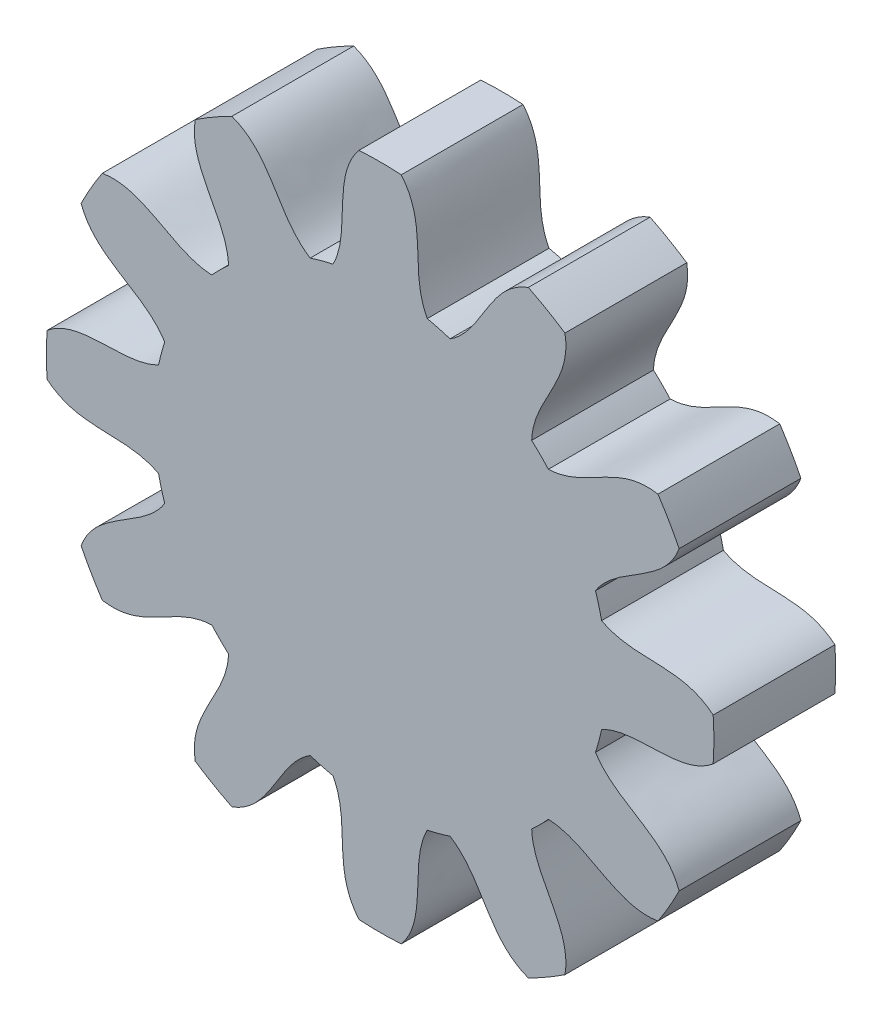
SolidWorks part; units mm, degrees
ref_plane "前视基准面" through (0, 0, 0) normal (0, 0, 1) x (1, 0, 0)
ref_plane "上视基准面" through (0, 0, 0) normal (0, 1, 0) x (1, 0, 0)
ref_plane "右视基准面" through (0, 0, 0) normal (1, 0, 0) x (0, 0, -1)
sketch "草图1" plane through (0, 0, 0) normal (0, 0, 1) x (1, 0, 0)
  line L0 (0, 11.2324) -> (0, -12.9546) construction
  line L1 (0, 16.8486) -> (0, -19.4319) construction
  circle A0 centre (0, 0) radius 7.2 construction
  arc A1 (-3.7303, 7.5263) -> (-4.6528, 6.9937) centre (0, 0) ccw
  arc A2 (-1.1862, 5.5752) -> (-1.7603, 5.4214) centre (0, 0) ccw
  arc A3 (0.5326, 8.3831) -> (-0.5326, 8.3831) centre (0, 0) ccw
  arc A4 (1.7603, 5.4214) -> (1.1862, 5.5752) centre (0, 0) ccw
  arc A5 (4.6528, 6.9937) -> (3.7303, 7.5263) centre (0, 0) ccw
  arc A6 (4.2352, 3.8149) -> (3.8149, 4.2352) centre (0, 0) ccw
  arc A7 (7.5263, 3.7303) -> (6.9937, 4.6528) centre (0, 0) ccw
  arc A8 (5.5752, 1.1862) -> (5.4214, 1.7603) centre (0, 0) ccw
  arc A9 (8.3831, -0.5326) -> (8.3831, 0.5326) centre (0, 0) ccw
  arc A10 (5.4214, -1.7603) -> (5.5752, -1.1862) centre (0, 0) ccw
  arc A11 (6.9937, -4.6528) -> (7.5263, -3.7303) centre (0, 0) ccw
  arc A12 (3.8149, -4.2352) -> (4.2352, -3.8149) centre (0, 0) ccw
  arc A13 (3.7303, -7.5263) -> (4.6528, -6.9937) centre (0, 0) ccw
  arc A14 (1.1862, -5.5752) -> (1.7603, -5.4214) centre (0, 0) ccw
  arc A15 (-0.5326, -8.3831) -> (0.5326, -8.3831) centre (0, 0) ccw
  arc A16 (-1.7603, -5.4214) -> (-1.1862, -5.5752) centre (0, 0) ccw
  arc A17 (-4.6528, -6.9937) -> (-3.7303, -7.5263) centre (0, 0) ccw
  arc A18 (-4.2352, -3.8149) -> (-3.8149, -4.2352) centre (0, 0) ccw
  arc A19 (-7.5263, -3.7303) -> (-6.9937, -4.6528) centre (0, 0) ccw
  arc A20 (-5.5752, -1.1862) -> (-5.4214, -1.7603) centre (0, 0) ccw
  arc A21 (-8.3831, 0.5326) -> (-8.3831, -0.5326) centre (0, 0) ccw
  arc A22 (-5.4214, 1.7603) -> (-5.5752, 1.1862) centre (0, 0) ccw
  arc A23 (-6.9937, 4.6528) -> (-7.5263, 3.7303) centre (0, 0) ccw
  arc A24 (-3.8149, 4.2352) -> (-4.2352, 3.8149) centre (0, 0) ccw
  arc A25 (-2.6404, -8.1321) -> (-1.7793, -8.3628) centre (0, 0) ccw
  arc A26 (-11.2894, -5.5954) -> (-10.4905, -6.9792) centre (0, 0) ccw
  arc A27 (-12.5746, 0.7989) -> (-12.5746, -0.7989) centre (0, 0) ccw
  arc A28 (8.3628, 1.7793) -> (8.1321, 2.6404) centre (0, 0) ccw
  arc A29 (-10.4905, 6.9792) -> (-11.2894, 5.5954) centre (0, 0) ccw
  arc A30 (6.3527, 5.7224) -> (5.7224, 6.3527) centre (0, 0) ccw
  arc A31 (10.4905, -6.9792) -> (11.2894, -5.5954) centre (0, 0) ccw
  arc A32 (-5.7224, 6.3527) -> (-6.3527, 5.7224) centre (0, 0) ccw
  circle A33 centre (0, 0) radius 10.8 construction
  arc A34 (11.2894, 5.5954) -> (10.4905, 6.9792) centre (0, 0) ccw
  arc A35 (5.7224, -6.3527) -> (6.3527, -5.7224) centre (0, 0) ccw
  arc A36 (1.7793, -8.3628) -> (2.6404, -8.1321) centre (0, 0) ccw
  arc A37 (-1.7793, 8.3628) -> (-2.6404, 8.1321) centre (0, 0) ccw
  arc A38 (2.6404, 8.1321) -> (1.7793, 8.3628) centre (0, 0) ccw
  arc A39 (8.1321, -2.6404) -> (8.3628, -1.7793) centre (0, 0) ccw
  arc A40 (-8.1321, 2.6404) -> (-8.3628, 1.7793) centre (0, 0) ccw
  arc A41 (0.7989, 12.5746) -> (-0.7989, 12.5746) centre (0, 0) ccw
  arc A42 (5.5954, -11.2894) -> (6.9792, -10.4905) centre (0, 0) ccw
  arc A43 (-0.7989, -12.5746) -> (0.7989, -12.5746) centre (0, 0) ccw
  arc A44 (-6.3527, -5.7224) -> (-5.7224, -6.3527) centre (0, 0) ccw
  arc A45 (-8.3628, -1.7793) -> (-8.1321, -2.6404) centre (0, 0) ccw
  arc A46 (-5.5954, 11.2894) -> (-6.9792, 10.4905) centre (0, 0) ccw
  arc A47 (12.5746, -0.7989) -> (12.5746, 0.7989) centre (0, 0) ccw
  arc A48 (-6.9792, -10.4905) -> (-5.5954, -11.2894) centre (0, 0) ccw
  arc A49 (6.9792, 10.4905) -> (5.5954, 11.2894) centre (0, 0) ccw
  spline S0 degree 3 poles (-0.5326, 8.3831) (-1.2254, 7.5539) (-0.7219, 6.4463) (-1.1862, 5.5752) knots 0 0 0 0 1 1 1 1
  spline S1 degree 3 poles (0.5326, 8.3831) (1.2254, 7.5539) (0.7219, 6.4463) (1.1862, 5.5752) knots 0 0 0 0 1 1 1 1
  spline S2 degree 3 poles (3.7303, 7.5263) (2.7157, 7.1545) (2.598, 5.9436) (1.7603, 5.4214) knots 0 0 0 0 1 1 1 1
  spline S3 degree 3 poles (4.6528, 6.9937) (4.8381, 5.9291) (3.8484, 5.2217) (3.8149, 4.2352) knots 0 0 0 0 1 1 1 1
  spline S4 degree 3 poles (6.9937, 4.6528) (5.9291, 4.8381) (5.2217, 3.8484) (4.2352, 3.8149) knots 0 0 0 0 1 1 1 1
  spline S5 degree 3 poles (7.5263, 3.7303) (7.1545, 2.7157) (5.9436, 2.598) (5.4214, 1.7603) knots 0 0 0 0 1 1 1 1
  spline S6 degree 3 poles (8.3831, 0.5326) (7.5539, 1.2254) (6.4463, 0.7219) (5.5752, 1.1862) knots 0 0 0 0 1 1 1 1
  spline S7 degree 3 poles (8.3831, -0.5326) (7.5539, -1.2254) (6.4463, -0.7219) (5.5752, -1.1862) knots 0 0 0 0 1 1 1 1
  spline S8 degree 3 poles (7.5263, -3.7303) (7.1545, -2.7157) (5.9436, -2.598) (5.4214, -1.7603) knots 0 0 0 0 1 1 1 1
  spline S9 degree 3 poles (6.9937, -4.6528) (5.9291, -4.8381) (5.2217, -3.8484) (4.2352, -3.8149) knots 0 0 0 0 1 1 1 1
  spline S10 degree 3 poles (4.6528, -6.9937) (4.8381, -5.9291) (3.8484, -5.2217) (3.8149, -4.2352) knots 0 0 0 0 1 1 1 1
  spline S11 degree 3 poles (3.7303, -7.5263) (2.7157, -7.1545) (2.598, -5.9436) (1.7603, -5.4214) knots 0 0 0 0 1 1 1 1
  spline S12 degree 3 poles (0.5326, -8.3831) (1.2254, -7.5539) (0.7219, -6.4463) (1.1862, -5.5752) knots 0 0 0 0 1 1 1 1
  spline S13 degree 3 poles (-0.5326, -8.3831) (-1.2254, -7.5539) (-0.7219, -6.4463) (-1.1862, -5.5752) knots 0 0 0 0 1 1 1 1
  spline S14 degree 3 poles (-3.7303, -7.5263) (-2.7157, -7.1545) (-2.598, -5.9436) (-1.7603, -5.4214) knots 0 0 0 0 1 1 1 1
  spline S15 degree 3 poles (-4.6528, -6.9937) (-4.8381, -5.9291) (-3.8484, -5.2217) (-3.8149, -4.2352) knots 0 0 0 0 1 1 1 1
  spline S16 degree 3 poles (-6.9937, -4.6528) (-5.9291, -4.8381) (-5.2217, -3.8484) (-4.2352, -3.8149) knots 0 0 0 0 1 1 1 1
  spline S17 degree 3 poles (-7.5263, -3.7303) (-7.1545, -2.7157) (-5.9436, -2.598) (-5.4214, -1.7603) knots 0 0 0 0 1 1 1 1
  spline S18 degree 3 poles (-8.3831, -0.5326) (-7.5539, -1.2254) (-6.4463, -0.7219) (-5.5752, -1.1862) knots 0 0 0 0 1 1 1 1
  spline S19 degree 3 poles (-8.3831, 0.5326) (-7.5539, 1.2254) (-6.4463, 0.7219) (-5.5752, 1.1862) knots 0 0 0 0 1 1 1 1
  spline S20 degree 3 poles (-7.5263, 3.7303) (-7.1545, 2.7157) (-5.9436, 2.598) (-5.4214, 1.7603) knots 0 0 0 0 1 1 1 1
  spline S21 degree 3 poles (-6.9937, 4.6528) (-5.9291, 4.8381) (-5.2217, 3.8484) (-4.2352, 3.8149) knots 0 0 0 0 1 1 1 1
  spline S22 degree 3 poles (-4.6528, 6.9937) (-4.8381, 5.9291) (-3.8484, 5.2217) (-3.8149, 4.2352) knots 0 0 0 0 1 1 1 1
  spline S23 degree 3 poles (-3.7303, 7.5263) (-2.7157, 7.1545) (-2.598, 5.9436) (-1.7603, 5.4214) knots 0 0 0 0 1 1 1 1
  spline S24 degree 3 poles (6.9792, -10.4905) (7.2572, -8.8937) (5.7725, -7.8326) (5.7224, -6.3527) knots 0 0 0 0 1 1 1 1
  spline S25 degree 3 poles (-12.5746, -0.7989) (-11.3308, -1.8381) (-9.6695, -1.0829) (-8.3628, -1.7793) knots 0 0 0 0 1 1 1 1
  spline S26 degree 3 poles (12.5746, -0.7989) (11.3308, -1.8381) (9.6695, -1.0829) (8.3628, -1.7793) knots 0 0 0 0 1 1 1 1
  spline S27 degree 3 poles (-12.5746, 0.7989) (-11.3308, 1.8381) (-9.6695, 1.0829) (-8.3628, 1.7793) knots 0 0 0 0 1 1 1 1
  spline S28 degree 3 poles (5.5954, 11.2894) (4.0736, 10.7318) (3.8969, 8.9154) (2.6404, 8.1321) knots 0 0 0 0 1 1 1 1
  spline S29 degree 3 poles (-11.2894, -5.5954) (-10.7318, -4.0736) (-8.9154, -3.8969) (-8.1321, -2.6404) knots 0 0 0 0 1 1 1 1
  spline S30 degree 3 poles (10.4905, -6.9792) (8.8937, -7.2572) (7.8326, -5.7725) (6.3527, -5.7224) knots 0 0 0 0 1 1 1 1
  spline S31 degree 3 poles (-11.2894, 5.5954) (-10.7318, 4.0736) (-8.9154, 3.8969) (-8.1321, 2.6404) knots 0 0 0 0 1 1 1 1
  spline S32 degree 3 poles (-5.5954, -11.2894) (-4.0736, -10.7318) (-3.8969, -8.9154) (-2.6404, -8.1321) knots 0 0 0 0 1 1 1 1
  spline S33 degree 3 poles (-10.4905, 6.9792) (-8.8937, 7.2572) (-7.8326, 5.7725) (-6.3527, 5.7224) knots 0 0 0 0 1 1 1 1
  spline S34 degree 3 poles (-0.7989, 12.5746) (-1.8381, 11.3308) (-1.0829, 9.6695) (-1.7793, 8.3628) knots 0 0 0 0 1 1 1 1
  spline S35 degree 3 poles (0.7989, -12.5746) (1.8381, -11.3308) (1.0829, -9.6695) (1.7793, -8.3628) knots 0 0 0 0 1 1 1 1
  spline S36 degree 3 poles (-0.7989, -12.5746) (-1.8381, -11.3308) (-1.0829, -9.6695) (-1.7793, -8.3628) knots 0 0 0 0 1 1 1 1
  spline S37 degree 3 poles (6.9792, 10.4905) (7.2572, 8.8937) (5.7725, 7.8326) (5.7224, 6.3527) knots 0 0 0 0 1 1 1 1
  spline S38 degree 3 poles (11.2894, -5.5954) (10.7318, -4.0736) (8.9154, -3.8969) (8.1321, -2.6404) knots 0 0 0 0 1 1 1 1
  spline S39 degree 3 poles (-10.4905, -6.9792) (-8.8937, -7.2572) (-7.8326, -5.7725) (-6.3527, -5.7224) knots 0 0 0 0 1 1 1 1
  spline S40 degree 3 poles (12.5746, 0.7989) (11.3308, 1.8381) (9.6695, 1.0829) (8.3628, 1.7793) knots 0 0 0 0 1 1 1 1
  spline S41 degree 3 poles (5.5954, -11.2894) (4.0736, -10.7318) (3.8969, -8.9154) (2.6404, -8.1321) knots 0 0 0 0 1 1 1 1
  spline S42 degree 3 poles (-6.9792, -10.4905) (-7.2572, -8.8937) (-5.7725, -7.8326) (-5.7224, -6.3527) knots 0 0 0 0 1 1 1 1
  spline S43 degree 3 poles (-5.5954, 11.2894) (-4.0736, 10.7318) (-3.8969, 8.9154) (-2.6404, 8.1321) knots 0 0 0 0 1 1 1 1
  spline S44 degree 3 poles (0.7989, 12.5746) (1.8381, 11.3308) (1.0829, 9.6695) (1.7793, 8.3628) knots 0 0 0 0 1 1 1 1
  spline S45 degree 3 poles (10.4905, 6.9792) (8.8937, 7.2572) (7.8326, 5.7725) (6.3527, 5.7224) knots 0 0 0 0 1 1 1 1
  spline S46 degree 3 poles (11.2894, 5.5954) (10.7318, 4.0736) (8.9154, 3.8969) (8.1321, 2.6404) knots 0 0 0 0 1 1 1 1
  spline S47 degree 3 poles (-6.9792, 10.4905) (-7.2572, 8.8937) (-5.7725, 7.8326) (-5.7224, 6.3527) knots 0 0 0 0 1 1 1 1
  point P7 (0, 7.1931)
  point P8 (0.9389, 7.1315)
  point P11 (1.8617, 6.948)
  point P12 (2.7527, 6.6455)
  point P13 (3.5965, 6.2294)
  point P14 (4.3789, 5.7066)
  point P15 (5.0863, 5.0863)
  point P16 (5.7066, 4.3789)
  point P17 (6.2294, 3.5965)
  point P18 (6.6455, 2.7527)
  point P19 (6.948, 1.8617)
  point P20 (7.1315, 0.9389)
  point P21 (7.1931, 0)
  point P22 (7.1315, -0.9389)
  point P23 (6.948, -1.8617)
  point P24 (6.6455, -2.7527)
  point P25 (6.2294, -3.5965)
  point P26 (5.7066, -4.3789)
  point P27 (5.0863, -5.0863)
  point P28 (4.3789, -5.7066)
  point P29 (3.5965, -6.2294)
  point P30 (2.7527, -6.6455)
  point P31 (1.8617, -6.948)
  point P32 (0.9389, -7.1315)
  point P33 (0, -7.1931)
  point P34 (-0.9389, -7.1315)
  point P35 (-1.8617, -6.948)
  point P36 (-2.7527, -6.6455)
  point P37 (-3.5965, -6.2294)
  point P38 (-4.3789, -5.7066)
  point P39 (-5.0863, -5.0863)
  point P40 (-5.7066, -4.3789)
  point P41 (-6.2294, -3.5965)
  point P42 (-6.6455, -2.7527)
  point P43 (-6.948, -1.8617)
  point P44 (-7.1315, -0.9389)
  point P45 (-7.1931, 0)
  point P46 (-7.1315, 0.9389)
  point P47 (-6.948, 1.8617)
  point P48 (-6.6455, 2.7527)
  point P49 (-6.2294, 3.5965)
  point P50 (-5.7066, 4.3789)
  point P51 (-5.0863, 5.0863)
  point P52 (-4.3789, 5.7066)
  point P53 (-3.5965, 6.2294)
  point P54 (-2.7527, 6.6455)
  point P55 (-1.8617, 6.948)
  point P56 (-0.9389, 7.1315)
  point P153 (0, 10.7896)
  point P154 (1.4083, 10.6973)
  point P157 (2.7925, 10.4219)
  point P158 (4.129, 9.9683)
  point P159 (5.3948, 9.344)
  point P160 (6.5683, 8.5599)
  point P161 (7.6294, 7.6294)
  point P162 (8.5599, 6.5683)
  point P163 (9.344, 5.3948)
  point P164 (9.9683, 4.129)
  point P165 (10.4219, 2.7925)
  point P166 (10.6973, 1.4083)
  point P167 (10.7896, 0)
  point P168 (10.6973, -1.4083)
  point P169 (10.4219, -2.7925)
  point P170 (9.9683, -4.129)
  point P171 (9.344, -5.3948)
  point P172 (8.5599, -6.5683)
  point P173 (7.6294, -7.6294)
  point P174 (6.5683, -8.5599)
  point P175 (5.3948, -9.344)
  point P176 (4.129, -9.9683)
  point P177 (2.7925, -10.4219)
  point P178 (1.4083, -10.6973)
  point P179 (0, -10.7896)
  point P180 (-1.4083, -10.6973)
  point P181 (-2.7925, -10.4219)
  point P182 (-4.129, -9.9683)
  point P183 (-5.3948, -9.344)
  point P184 (-6.5683, -8.5599)
  point P185 (-7.6294, -7.6294)
  point P186 (-8.5599, -6.5683)
  point P187 (-9.344, -5.3948)
  point P188 (-9.9683, -4.129)
  point P189 (-10.4219, -2.7925)
  point P190 (-10.6973, -1.4083)
  point P191 (-10.7896, 0)
  point P192 (-10.6973, 1.4083)
  point P193 (-10.4219, 2.7925)
  point P194 (-9.9683, 4.129)
  point P195 (-9.344, 5.3948)
  point P196 (-8.5599, 6.5683)
  point P197 (-7.6294, 7.6294)
  point P198 (-6.5683, 8.5599)
  point P199 (-5.3948, 9.344)
  point P200 (-4.129, 9.9683)
  point P201 (-2.7925, 10.4219)
  point P202 (-1.4083, 10.6973)
  dimension "D1" = 14.4
  dimension "D2" = 16.8
  dimension "D3" = 11.4
extrude "凸台-拉伸1" add sketch "草图1" along normal blind 1 and the other way blind 3.5979 contours A46 S47 A32 S33 A29 S31 A40 S27 A27 S25 A45 S29 A26 S39 A44 S42 A48 S32 A25 S36 A43 S35 A36 S41 A42 S24 A35 S30 A31 S38 A39 S26 A47 S40 A28 S46 A34 S45 A30 S37 A49 S28 A38 S44 A41 S34 A37 S43 A1 S23
sketch "草图2" plane through (0, 0, -3.5979) normal (0, 0, -1) x (-1, 0, 0)
  circle A0 centre (0, 0) radius 2.5
  dimension "D1" = 5
extrude "切除-拉伸1" cut sketch "草图2" against normal blind 1
